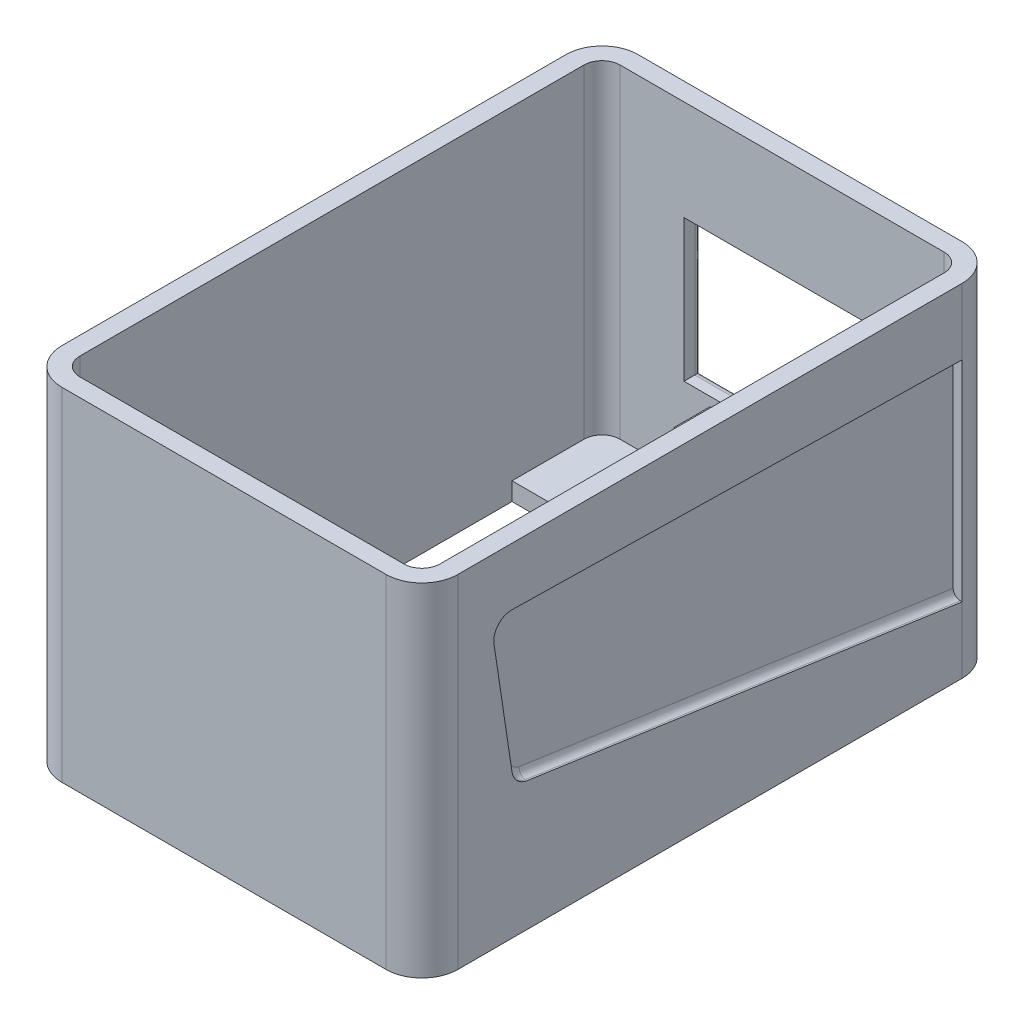
SolidWorks part; units mm, degrees
material "ABS"
ref_plane "Front Plane" through (0, 0, 0) normal (0, 0, 1) x (1, 0, 0)
ref_plane "Top Plane" through (0, 0, 0) normal (0, 1, 0) x (1, 0, 0)
ref_plane "Right Plane" through (0, 0, 0) normal (1, 0, 0) x (0, 0, -1)
sketch "Sketch1" plane through (0, 0, 0) normal (0, 1, 0) x (1, 0, 0)
  line L0 (-57.4475, 24.4561) -> (-57.4475, -102.5439)
  line L1 (-51.0975, 62.5561) -> (63.2025, 62.5561)
  line L2 (-63.7975, 49.8561) -> (-63.7975, -127.9439)
  line L3 (-51.0975, -140.6439) -> (63.2025, -140.6439)
  line L4 (75.9025, 49.8561) -> (75.9025, -127.9439)
  line L5 (-19.3475, -134.2939) -> (31.4525, -134.2939)
  line L6 (69.5525, 24.4561) -> (69.5525, -102.5439)
  line L7 (-19.3475, 56.2061) -> (31.4525, 56.2061)
  line L8 (-57.4475, 49.8561) -> (-57.4475, -127.9439) construction
  line L10 (-19.3475, 56.2061) -> (-19.3475, 24.4561)
  line L11 (-19.3475, 24.4561) -> (-57.4475, 24.4561)
  line L13 (-51.0975, 56.2061) -> (63.2025, 56.2061) construction
  line L14 (31.4525, 56.2061) -> (31.4525, 24.4561)
  line L15 (31.4525, 24.4561) -> (69.5525, 24.4561)
  line L16 (69.5525, -102.5439) -> (31.4525, -102.5439)
  line L17 (31.4525, -102.5439) -> (31.4525, -134.2939)
  line L18 (-57.4475, -102.5439) -> (-19.3475, -102.5439)
  line L19 (-19.3475, -102.5439) -> (-19.3475, -134.2939)
  line L20 (69.5525, 49.8561) -> (69.5525, -127.9439) construction
  line L21 (-51.0975, -134.2939) -> (63.2025, -134.2939) construction
  arc A0 (-63.7975, -127.9439) -> (-51.0975, -140.6439) centre (-51.0975, -127.9439) ccw
  arc A1 (63.2025, -140.6439) -> (75.9025, -127.9439) centre (63.2025, -127.9439) ccw
  arc A2 (63.2025, 62.5561) -> (75.9025, 49.8561) centre (63.2025, 49.8561) cw
  arc A3 (-51.0975, 62.5561) -> (-63.7975, 49.8561) centre (-51.0975, 49.8561) ccw
  arc A8 (-51.0975, 56.2061) -> (-57.4475, 49.8561) centre (-51.0975, 49.8561) ccw construction
  arc A9 (63.2025, 56.2061) -> (69.5525, 49.8561) centre (63.2025, 49.8561) cw construction
  arc A10 (-57.4475, -127.9439) -> (-51.0975, -134.2939) centre (-51.0975, -127.9439) ccw construction
  arc A11 (63.2025, -134.2939) -> (69.5525, -127.9439) centre (63.2025, -127.9439) ccw construction
  point P6 (-63.7975, -140.6439)
  point P11 (75.9025, 62.5561)
  point P14 (-63.7975, 62.5561)
  dimension "D3" = 12.7
  dimension "D1" = 203.2
  dimension "D2" = 139.7
  dimension "D5" = 38.1
  dimension "D6" = 31.75
  dimension "D7" = 31.75
  dimension "D8" = 38.1
  dimension "D4" = 6.35
extrude "Boss-Extrude1" add sketch "Sketch1" along normal blind 6.35 contours L2 A0 L3 A1 L4 A2 L1 A3
sketch "Sketch2" plane through (0, 6.35, 0) normal (0, 1, 0) x (1, 0, 0)
  line L0 (75.9025, -127.9439) -> (75.9025, 49.8561)
  line L2 (63.2025, 62.5561) -> (-51.0975, 62.5561)
  line L4 (-63.7975, 49.8561) -> (-63.7975, -127.9439)
  line L6 (-51.0975, -140.6439) -> (63.2025, -140.6439)
  line L8 (69.5525, -127.9439) -> (69.5525, 49.8561)
  line L9 (63.2025, 56.2061) -> (-51.0975, 56.2061)
  line L10 (-57.4475, 49.8561) -> (-57.4475, -127.9439)
  line L11 (-51.0975, -134.2939) -> (63.2025, -134.2939)
  arc A0 (-51.0975, -140.6439) -> (-63.7975, -127.9439) centre (-51.0975, -127.9439) cw
  arc A1 (-63.7975, 49.8561) -> (-51.0975, 62.5561) centre (-51.0975, 49.8561) cw
  arc A2 (63.2025, 62.5561) -> (75.9025, 49.8561) centre (63.2025, 49.8561) cw
  arc A3 (75.9025, -127.9439) -> (63.2025, -140.6439) centre (63.2025, -127.9439) cw
  arc A4 (63.2025, 56.2061) -> (69.5525, 49.8561) centre (63.2025, 49.8561) cw
  arc A5 (-57.4475, 49.8561) -> (-51.0975, 56.2061) centre (-51.0975, 49.8561) cw
  arc A6 (-51.0975, -134.2939) -> (-57.4475, -127.9439) centre (-51.0975, -127.9439) cw
  arc A7 (69.5525, -127.9439) -> (63.2025, -134.2939) centre (63.2025, -127.9439) cw
  dimension "D1" = 6.35
extrude "Boss-Extrude2" add sketch "Sketch2" along normal blind 114.3 contours L8 A4 L9 A5 L10 A6 L11 A7
sketch "Sketch3" plane through (0, 0, -62.5561) normal (0, 0, -1) x (-1, 0, 0)
  line L0 (-63.2025, 120.65) -> (51.0975, 120.65) construction
  line L1 (-40.6525, 85.325) -> (28.5475, 85.325)
  line L2 (-40.6525, 85.325) -> (-40.6525, 35.325)
  line L3 (-40.6525, 35.325) -> (28.5475, 35.325)
  line L4 (28.5475, 85.325) -> (28.5475, 35.325)
  line L5 (-40.6525, 85.325) -> (28.5475, 35.325) construction
  line L6 (-40.6525, 35.325) -> (28.5475, 85.325) construction
  line L7 (-6.0525, 60.325) -> (51.0975, 60.325) construction
  line L8 (51.0975, 120.65) -> (51.0975, 0) construction
  line L9 (-6.0525, 60.325) -> (-6.0525, 120.65) construction
  point P0 (-6.0525, 60.325)
  dimension "D1" = 69.2
  dimension "D2" = 50
extrude "Cut-Extrude1" cut sketch "Sketch3" against normal blind 31.71 contours L1 L4 L3 L2
fillet "Fillet1" radius 2.54 4 edges at (-28.5475, 60.325, -62.5561) (6.0525, 85.325, -62.5561) (40.6525, 60.325, -62.5561) (6.0525, 35.325, -62.5561)
sketch "Sketch6" plane through (-63.7975, 0, 0) normal (-1, 0, 0) x (0, 0, 1)
  line L0 (-49.8561, 23.368) -> (103.5197, 45.4589)
  line L1 (-49.8561, 120.65) -> (-49.8561, 0) construction
  line L2 (108.8939, 50.8) -> (115.2439, 93.0371)
  line L3 (108.8425, 100.33) -> (-49.8561, 97.282)
  line L4 (-49.8561, 120.65) -> (127.9439, 120.65) construction
  line L5 (127.9439, 120.65) -> (127.9439, 0) construction
  line L6 (-49.8561, 0) -> (127.9439, 0) construction
  line L7 (-49.8561, 97.282) -> (-49.8561, 23.368)
  arc A0 (103.5197, 45.4589) -> (108.8939, 50.8) centre (102.6145, 51.7441) ccw
  arc A1 (115.2439, 93.0371) -> (108.8425, 100.33) centre (108.9645, 93.9812) ccw
  dimension "D1" = 6.35
  dimension "D2" = 23.368
  dimension "D3" = 20.32
  dimension "D4" = 12.7
  dimension "D5" = 19.05
  dimension "D6" = 23.368
  dimension "D7" = 50.8
extrude "Cut-Extrude2" cut sketch "Sketch6" against normal blind 3.175 contours L3 L7 L0 A0 L2 A1
fillet "Fillet2" radius 2.54 6 edges at (-60.6225, 98.806, 29.4932) (-60.6225, 98.1701, 113.7368) (-60.6225, 71.9186, 112.0689) (-60.6225, 47.2401, 107.0907) (-60.6225, 60.325, -49.8561) (-60.6225, 34.4135, 26.8318)
sketch "Sketch8" plane through (0, 0, -56.2061) normal (0, 0, 1) x (1, 0, 0)
  line L1 (31.4525, 32.15) -> (-19.3475, 32.15)
  line L2 (31.4525, 32.15) -> (31.4525, 25.8)
  line L3 (31.4525, 25.8) -> (-19.3475, 25.8)
  line L4 (-19.3475, 32.15) -> (-19.3475, 25.8)
  line L5 (31.4525, 32.15) -> (-19.3475, 25.8) construction
  line L6 (31.4525, 25.8) -> (-19.3475, 32.15) construction
  line L7 (-28.5475, 35.325) -> (40.6525, 35.325) construction
  line L8 (-19.3475, 6.35) -> (-19.3475, 0) construction
  line L9 (31.4525, 6.35) -> (31.4525, 0) construction
  point P0 (6.0525, 28.975)
  dimension "D1" = 6.35
  dimension "D2" = 3.175
extrude "Boss-Extrude3" add sketch "Sketch8" along normal blind 12.7
sketch "Sketch9" plane through (0, 32.15, 0) normal (0, 1, 0) x (1, 0, 0)
  line L1 (31.4525, 43.5061) -> (4.1505, 43.5061)
  line L2 (31.4525, 43.5061) -> (31.4525, 46.6811)
  line L3 (31.4525, 46.6811) -> (4.1505, 46.6811)
  line L5 (4.1505, 43.5061) -> (4.1505, 46.6811)
  dimension "D1" = 3.175
extrude "Boss-Extrude4" add sketch "Sketch9" along normal blind 6.35
fillet "Fillet4" radius 2.54 1 edges at (6.0525, 25.8, -56.2061)
sketch3d "3DSketch2"
  line L0 (6.0525, 120.65, -62.5561) -> (6.0525, 120.65, -5.2386) construction
  line L1 (63.2025, 120.65, -62.5561) -> (-51.0975, 120.65, -62.5561) construction
  line L2 (6.0525, 120.65, -5.2386) -> (6.0525, 102.4554, -5.2386) construction
ref_plane "Plane1" through (6.0525, 0, 0) normal (1, 0, 0) x (0, 0, -1)
mirror "Mirror2" about plane through (6.0525, 0, 0) normal (1, 0, 0) of "Cut-Extrude2"
fillet "Fillet5" radius 2.54 5 edges at (72.7275, 34.4135, 26.8318) (72.7275, 47.2401, 107.0907) (72.7275, 98.806, 29.4932) (72.7275, 98.1701, 113.7368) (72.7275, 71.9186, 112.0689)
